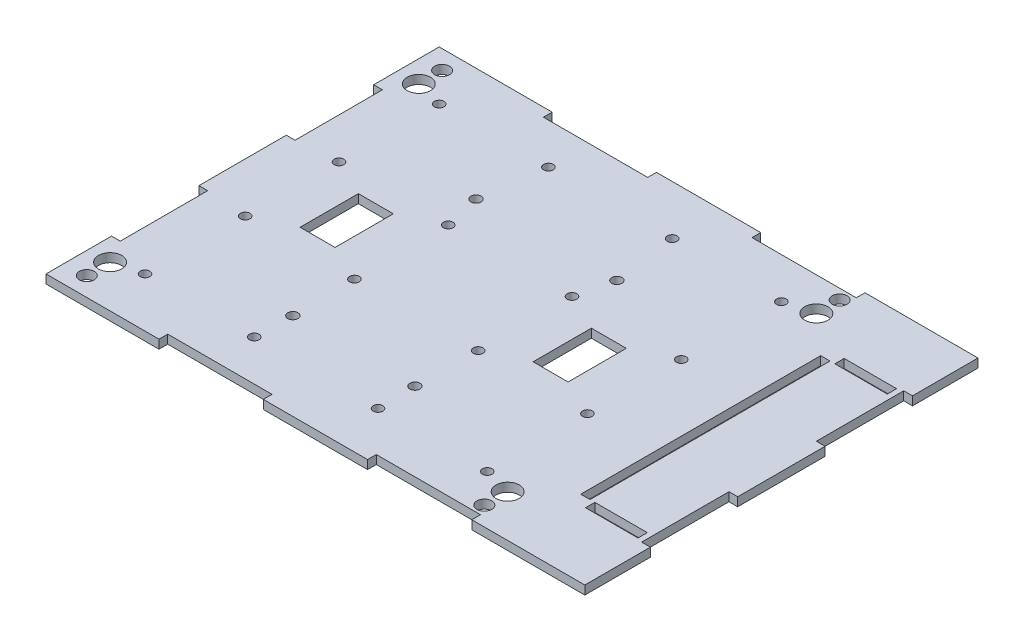
SolidWorks part; units mm, degrees
ref_plane "Front Plane" through (0, 0, 0) normal (0, 0, 1) x (1, 0, 0)
ref_plane "Top Plane" through (0, 0, 0) normal (0, 1, 0) x (1, 0, 0)
ref_plane "Right Plane" through (0, 0, 0) normal (1, 0, 0) x (0, 0, -1)
sketch "Sketch1" plane through (0, 0, 0) normal (0, 1, 0) x (1, 0, 0)
  line L0 (92.5, 0) -> (92.5, -64.5) construction
  line L1 (3, 0) -> (38.8, 0)
  line L2 (0, -3) -> (0, -22.5)
  line L3 (3, -135) -> (38.8, -135)
  line L4 (185, -3) -> (185, -22.5)
  line L5 (92.5, -64.5) -> (0, -64.5) construction
  line L6 (92.5, -132) -> (92.5, -67.5) construction
  line L8 (0, -64.5) -> (0, -70.5)
  line L11 (92.5, -67.5) -> (185, -67.5) construction
  line L12 (160.5, -26.3) -> (157.3, -26.3)
  line L14 (185, -67.5) -> (185, -74.5)
  line L19 (160.5, -26.3) -> (160.5, -108.7)
  line L20 (160.5, -108.7) -> (157.3, -108.7)
  line L21 (157.3, -26.3) -> (157.3, -108.7)
  line L22 (180.15, -108.7) -> (162.15, -108.7)
  line L23 (180.15, -23.1) -> (162.15, -23.1)
  line L24 (180.15, -23.1) -> (180.15, -26.3)
  line L25 (180.15, -26.3) -> (162.15, -26.3)
  line L26 (162.15, -23.1) -> (162.15, -26.3)
  line L27 (180.15, -108.7) -> (180.15, -111.9)
  line L28 (180.15, -111.9) -> (162.15, -111.9)
  line L29 (162.15, -108.7) -> (162.15, -111.9)
  line L30 (3, -22.5) -> (3, -52.5)
  line L55 (3, -52.5) -> (0, -52.5)
  line L56 (3, -22.5) -> (0, -22.5)
  line L57 (3, -82.5) -> (3, -112.5)
  line L58 (3, -82.5) -> (0, -82.5)
  line L59 (3, -112.5) -> (0, -112.5)
  line L60 (0, -52.5) -> (0, -82.5)
  line L61 (0, -112.5) -> (0, -132)
  line L62 (38.8, 0) -> (38.8, -3)
  line L63 (38.8, -3) -> (74.6, -3)
  line L64 (74.6, -3) -> (74.6, 0)
  line L65 (146.2, -3) -> (146.2, 0)
  line L66 (110.4, -3) -> (146.2, -3)
  line L67 (110.4, 0) -> (110.4, -3)
  line L72 (146.2, 0) -> (182, 0)
  line L73 (74.6, 0) -> (110.4, 0)
  line L74 (38.8, -135) -> (38.8, -132)
  line L75 (38.8, -132) -> (74.6, -132)
  line L76 (74.6, -132) -> (74.6, -135)
  line L78 (146.2, -132) -> (146.2, -135)
  line L79 (110.4, -132) -> (146.2, -132)
  line L80 (110.4, -135) -> (110.4, -132)
  line L85 (146.2, -135) -> (182, -135)
  line L86 (74.6, -135) -> (110.4, -135)
  line L87 (185, -22.5) -> (182, -22.5)
  line L88 (182, -22.5) -> (182, -52.5)
  line L89 (182, -52.5) -> (185, -52.5)
  line L90 (185, -82.5) -> (182, -82.5)
  line L91 (182, -82.5) -> (182, -112.5)
  line L92 (182, -112.5) -> (185, -112.5)
  line L93 (185, -52.5) -> (185, -82.5)
  line L94 (185, -112.5) -> (185, -132)
  line L96 (121.75, -57.5) -> (109.75, -57.5)
  line L97 (121.75, -57.5) -> (121.75, -77.5)
  line L98 (121.75, -77.5) -> (109.75, -77.5)
  line L99 (109.75, -57.5) -> (109.75, -77.5)
  line L100 (41.75, -57.5) -> (29.75, -57.5)
  line L101 (41.75, -57.5) -> (41.75, -77.5)
  line L102 (41.75, -77.5) -> (29.75, -77.5)
  line L103 (29.75, -57.5) -> (29.75, -77.5)
  line L104 (217.8, -3) -> (217.8, 0) [skipped]
  line L105 (217.8, -132) -> (217.8, -135) [skipped]
  line L107 (3, 0) -> (0, 0)
  line L108 (0, 0) -> (0, -3)
  line L109 (182, 0) -> (185, 0)
  line L110 (185, 0) -> (185, -3)
  line L112 (182, 0) -> (182, -3) [skipped]
  line L113 (182, -3) -> (185, -3) [skipped]
  line L115 (182, -135) -> (185, -135)
  line L116 (185, -135) -> (185, -132)
  line L117 (0, -132) -> (0, -135)
  line L118 (182, -132) -> (185, -132) [skipped]
  line L119 (182, -135) -> (182, -132) [skipped]
  line L120 (0, -135) -> (3, -135)
  circle A0 centre (17, -118) radius 1.65
  circle A1 centre (17, -83.6) radius 1.65
  circle A2 centre (17, -51.4) radius 1.65
  circle A3 centre (17, -17) radius 1.65
  circle A4 centre (54.5, -17) radius 1.65
  circle A5 centre (54.5, -51.4) radius 1.65
  circle A6 centre (54.5, -83.6) radius 1.65
  circle A7 centre (54.5, -118) radius 1.65
  circle A8 centre (97, -118) radius 1.65
  circle A9 centre (97, -83.6) radius 1.65
  circle A10 centre (97, -51.4) radius 1.65
  circle A11 centre (97, -17) radius 1.65
  circle A12 centre (134.5, -51.4) radius 1.65
  circle A13 centre (134.5, -17) radius 1.65
  circle A14 centre (134.5, -83.6) radius 1.65
  circle A15 centre (134.5013, -118) radius 1.65
  circle A16 centre (7.5, -6.5) radius 2.55
  circle A17 centre (7.5, -128.5) radius 2.55
  circle A18 centre (144.0013, -128.5) radius 2.55
  circle A19 centre (144, -6.5) radius 2.55
  circle A20 centre (7.5, -14.5) radius 4
  circle A21 centre (7.5, -120.5) radius 4
  circle A22 centre (144.0013, -120.5) radius 4
  circle A23 centre (144, -14.5) radius 4
  circle A24 centre (96.705, -105.03) radius 1.75
  circle A25 centre (54.795, -105.03) radius 1.75
  circle A26 centre (51.555, -38.93) radius 1.75
  circle A27 centre (99.945, -38.93) radius 1.75
  point P22 (160.5, -67.5)
  point P27 (162.15, -24.7)
  dimension "D58" = 3.3
  dimension "D59" = 3.3
  dimension "D60" = 3.3
  dimension "D61" = 3.3
  dimension "D62" = 3.3
  dimension "D63" = 3.3
  dimension "D64" = 3.3
  dimension "D65" = 3.3
  dimension "D66" = 3.3
  dimension "D67" = 3.3
  dimension "D68" = 3.3
  dimension "D69" = 3.3
  dimension "D70" = 3.3
  dimension "D71" = 3.3
  dimension "D72" = 3.3
  dimension "D73" = 3.3
  dimension "D34" = 5.1
  dimension "D35" = 5.1
  dimension "D36" = 5.1
  dimension "D37" = 5.1
  dimension "D42" = 8
  dimension "D45" = 8
  dimension "D55" = 8
  dimension "D56" = 8
  dimension "D75" = 0
  dimension "D83" = 3.5
  dimension "D84" = 3.5
  dimension "D85" = 3.5
  dimension "D86" = 3.5
  dimension "D3" = 64.5
  dimension "D6" = 64.5
  dimension "D8" = 1.85
  dimension "D9" = 1.65
  dimension "D10" = 82.4
  dimension "D11" = 18
  dimension "D12" = 3.2
  dimension "D13" = 1.65
  dimension "D14" = 0
  dimension "D15" = 18
  dimension "D16" = 3.2
  dimension "D17" = 0
  dimension "D18" = 3
  dimension "D19" = 30
  dimension "D20" = 2
  dimension "D21" = 22.5
  dimension "D22" = 3
  dimension "D23" = 35.8
  dimension "D24" = 3
  dimension "D25" = 35.8
  dimension "D26" = 35.8
  dimension "D27" = 3
  dimension "D28" = 35.8
  dimension "D29" = 3
  dimension "D30" = 35.8
  dimension "D31" = 30
  dimension "D32" = 3
  dimension "D33" = 2
  dimension "D38" = 4.5
  dimension "D39" = 3.5
  dimension "D40" = 4.5
  dimension "D41" = 3.5
  dimension "D43" = 9.5
  dimension "D44" = 9.5
  dimension "D46" = 20
  dimension "D47" = 12
  dimension "D48" = 20
  dimension "D49" = 12
  dimension "D50" = 6.1
  dimension "D51" = 12.75
  dimension "D52" = 6.1
  dimension "D53" = 12.75
  dimension "D54" = 35.8
  dimension "D57" = 0
  dimension "D74" = 8
  dimension "D76" = 8
  dimension "D77" = 0
  dimension "D78" = 8
  dimension "D79" = 3.5
  dimension "D80" = 3.5
  dimension "D81" = 0
  dimension "D82" = 8
extrude "Boss-Extrude1" add sketch "Sketch1" along normal blind 3
